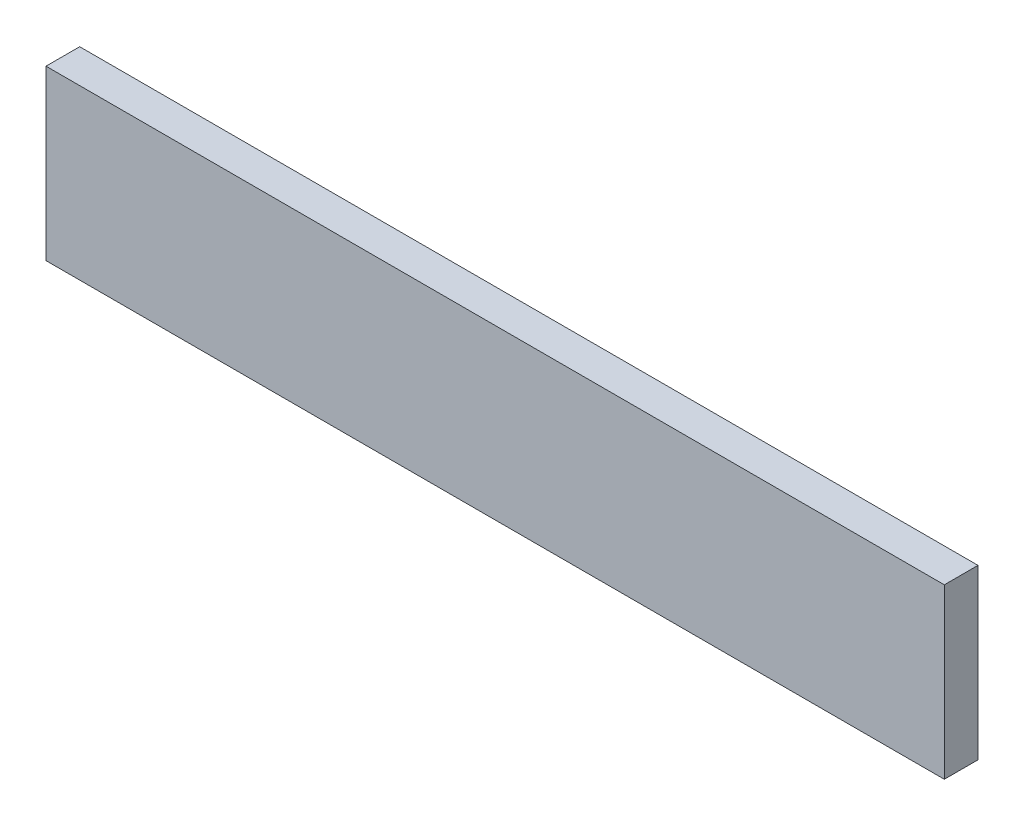
SolidWorks part; units mm, degrees
ref_plane "Plan de face" through (0, 0, 0) normal (0, 0, 1) x (1, 0, 0)
ref_plane "Plan de dessus" through (0, 0, 0) normal (0, 1, 0) x (1, 0, 0)
ref_plane "Plan de droite" through (0, 0, 0) normal (1, 0, 0) x (0, 0, -1)
sketch "Esquisse1" plane through (0, 0, 0) normal (0, 0, 1) x (1, 0, 0)
  line L1 (-40, -7.5) -> (40, -7.5)
  line L2 (-40, -7.5) -> (-40, 7.5)
  line L3 (-40, 7.5) -> (40, 7.5)
  line L4 (40, -7.5) -> (40, 7.5)
  line L5 (-40, -7.5) -> (40, 7.5) construction
  line L6 (-40, 7.5) -> (40, -7.5) construction
  point P0 (0, 0)
  dimension "D1" = 15
  dimension "D2" = 80
extrude "Boss.-Extru.1" add sketch "Esquisse1" along normal blind 3
